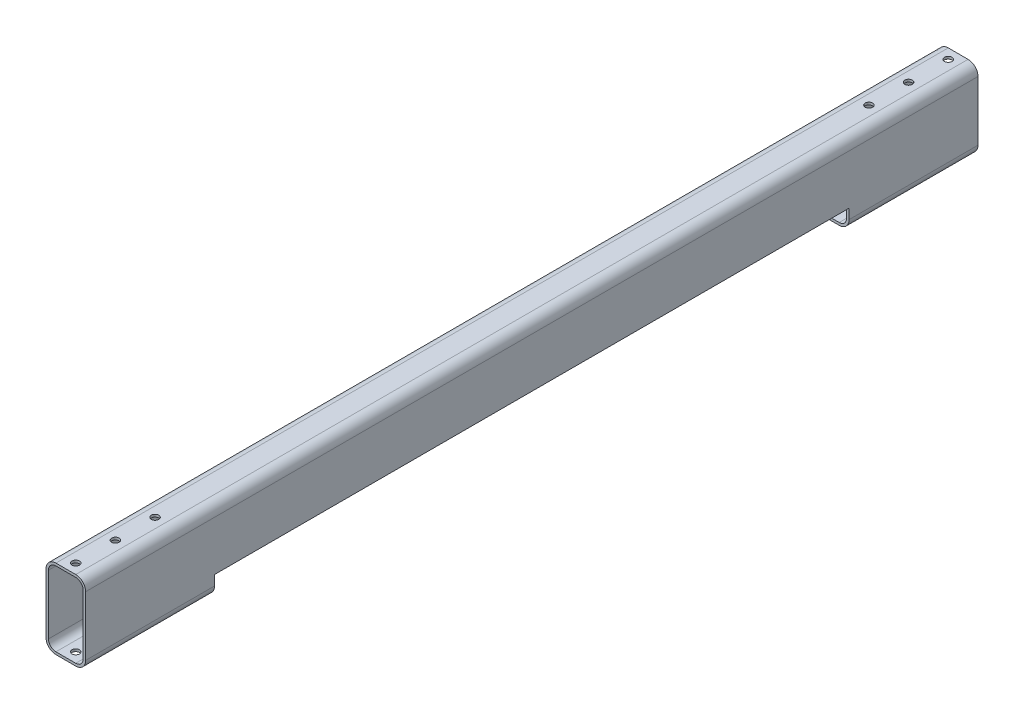
SolidWorks part; units mm, degrees
material "6061-T6 (SS)"
ref_plane "Front Plane" through (0, 0, 0) normal (0, 0, 1) x (1, 0, 0)
ref_plane "Top Plane" through (0, 0, 0) normal (0, 1, 0) x (1, 0, 0)
ref_plane "Right Plane" through (0, 0, 0) normal (1, 0, 0) x (0, 0, -1)
sketch "Sketch1" plane through (0, 0, 0) normal (0, 0, 1) x (1, 0, 0)
  line L1 (-6.35, -25.4) -> (6.35, -25.4)
  line L2 (-12.7, -19.05) -> (-12.7, 19.05)
  line L3 (-6.35, 25.4) -> (6.35, 25.4)
  line L4 (12.7, -19.05) -> (12.7, 19.05)
  line L5 (-12.7, -25.4) -> (12.7, 25.4) construction
  line L6 (-12.7, 25.4) -> (12.7, -25.4) construction
  arc A0 (-12.7, -19.05) -> (-6.35, -25.4) centre (-6.35, -19.05) ccw
  arc A1 (6.35, -25.4) -> (12.7, -19.05) centre (6.35, -19.05) ccw
  arc A2 (6.35, 25.4) -> (12.7, 19.05) centre (6.35, 19.05) cw
  arc A3 (-12.7, 19.05) -> (-6.35, 25.4) centre (-6.35, 19.05) cw
  point P0 (0, 0)
  dimension "D3" = 6.35
  dimension "D1" = 50.8
  dimension "D2" = 25.4
extrude "Extrude-Thin1" add sketch "Sketch1" along normal blind 571.5 thin thin type one direction reverse wall 1.5875
hole_wizard "3/16 (0.1875) Diameter Hole1" positions "3DSketch1" profile "Sketch3" hole size "3/16" standard "ANSI Inch" end condition through all
sketch3d "3DSketch1"
  line L1 (6.35, 25.4, 0) -> (-6.35, 25.4, 0) construction
  line L6 (0, 25.4, 571.5) -> (0, 25.4, 0) construction
  line L7 (6.35, 25.4, 571.5) -> (-6.35, 25.4, 571.5) construction
  point P57 (0, 25.4, 6.35)
  point P59 (0, 25.4, 31.75)
  point P61 (0, 25.4, 57.15)
  point P63 (0, 25.4, 539.75)
  point P65 (0, 25.4, 514.35)
  point P67 (0, 25.4, 565.15)
  dimension "D1" = 25.4
  dimension "D2" = 25.4
  dimension "D3" = 6.35
  dimension "D4" = 25.4
  dimension "D5" = 25.4
  dimension "D6" = 6.35
sketch "Sketch3" plane through (0, 25.4, 565.15) normal (1, 0, 0) x (0, 0, 1)
  line L0 (0, 0) -> (0, 50.8)
  line L1 (0, 50.8) -> (2.3812, 50.8)
  line L2 (2.3812, 50.8) -> (2.3812, 0)
  line L5 (2.3812, 0) -> (0, 0)
  line L11 (0, -6.35) -> (0, 107.95) construction
  dimension "Thru Hole Dia." = 4.7625
  dimension "Thru Hole Depth" = 50.8
sketch "Sketch5" plane through (12.7, 0, 0) normal (1, 0, 0) x (0, 0, -1)
  line L0 (-488.95, -12.7) -> (-488.95, -25.4)
  line L2 (-488.95, -25.4) -> (-82.55, -25.4)
  line L3 (-82.55, -25.4) -> (-82.55, -12.7)
  line L4 (-82.55, -12.7) -> (-488.95, -12.7)
  line L12 (-571.5, -25.4) -> (0, -25.4) construction
  point P0 (-524.0678, 0)
  point P2 (-523.9954, -1.8601)
  point P8 (-523.8121, -19.05)
  point P9 (0, 0)
  point P11 (-285.75, -25.4)
  point P12 (-285.75, -25.4)
  dimension "D1" = 12.7
  dimension "D2" = 406.4
extrude "Cut-Extrude1" cut sketch "Sketch5" against normal through all
hole_wizard "3/16 (0.195) Diameter Hole1" positions "Sketch6" profile "Sketch7" hole size "3/16" standard "ANSI Inch"
sketch "Sketch6" plane through (0, -25.4, 0) normal (0, -1, 0) x (-1, 0, 0)
  point P0 (2.54, -495.3)
  point P3 (-5.08, -502.92)
  point P6 (-5.08, -68.58)
  point P9 (2.54, -76.2)
sketch "Sketch7" plane through (-2.54, -25.4, 495.3) normal (1, 0, 0) x (0, 0, -1)
  line L0 (0, 0) -> (0, 26.888)
  line L1 (0, 26.888) -> (2.4765, 25.4)
  line L2 (2.4765, 25.4) -> (2.4765, 0)
  line L5 (2.4765, 0) -> (0, 0)
  line L10 (0, 26.888) -> (-2.4765, 25.4) construction
  line L11 (0, -6.35) -> (0, 107.95) construction
  dimension "Hole Dia." = 4.953
  dimension "Hole Depth" = 25.4
  dimension "Drill Angle" = 118
